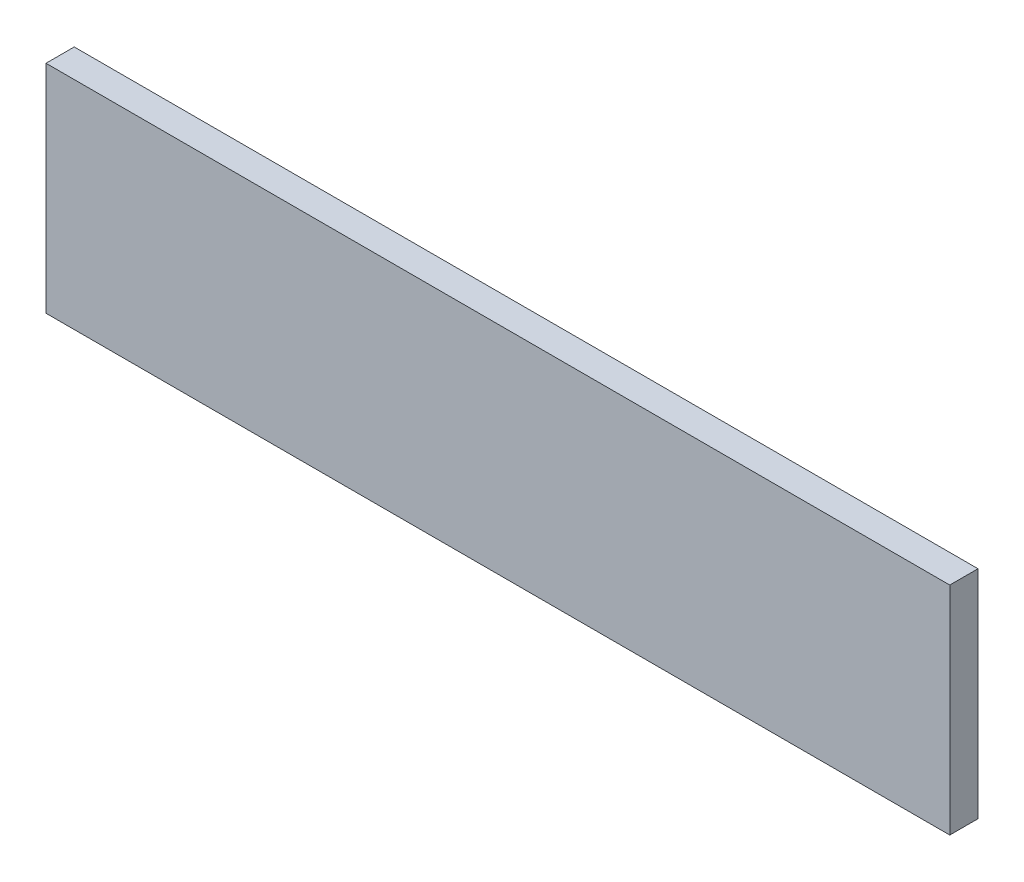
SolidWorks part; units mm, degrees
ref_plane "Front Plane" through (0, 0, 0) normal (0, 0, 1) x (1, 0, 0)
ref_plane "Top Plane" through (0, 0, 0) normal (0, 1, 0) x (1, 0, 0)
ref_plane "Right Plane" through (0, 0, 0) normal (1, 0, 0) x (0, 0, -1)
sketch "Sketch1" plane through (0, 0, 0) normal (0, 0, 1) x (1, 0, 0)
  line L1 (-304.8, 73.025) -> (304.8, 73.025)
  line L2 (-304.8, 73.025) -> (-304.8, -73.025)
  line L3 (-304.8, -73.025) -> (304.8, -73.025)
  line L4 (304.8, 73.025) -> (304.8, -73.025)
  line L5 (-304.8, 73.025) -> (304.8, -73.025) construction
  line L6 (-304.8, -73.025) -> (304.8, 73.025) construction
  point P0 (0, 0)
  dimension "D1" = 146.05
  dimension "D2" = 609.6
extrude "Boss-Extrude1" add sketch "Sketch1" along normal blind 19.05
